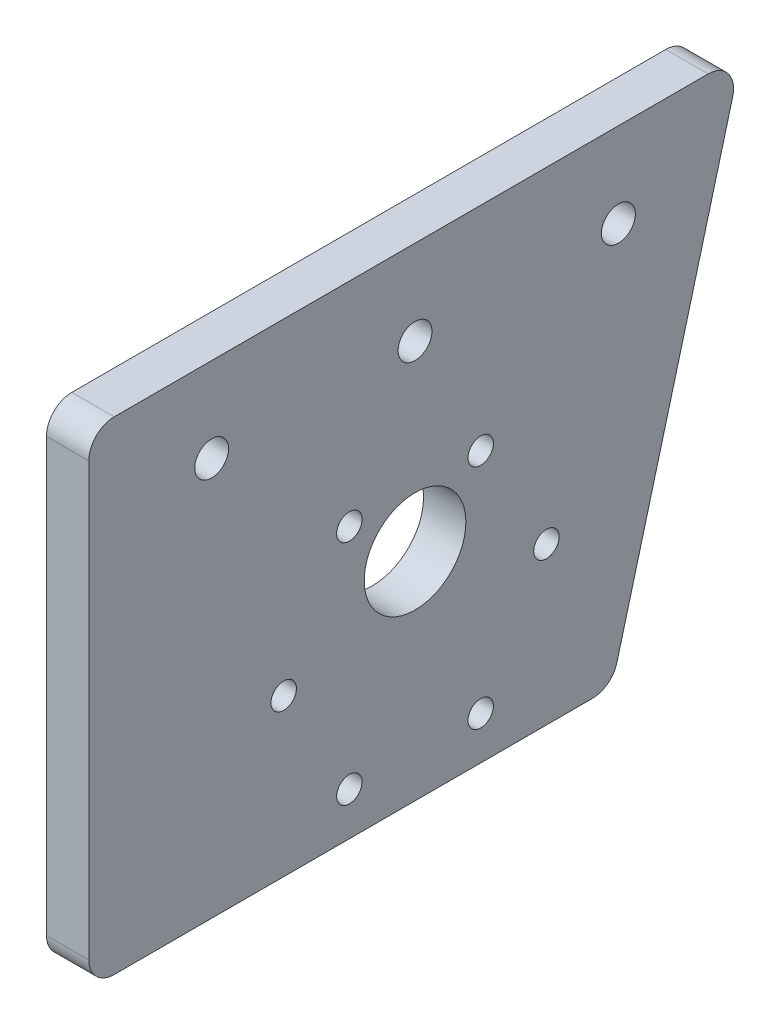
SolidWorks part; units mm, degrees
ref_plane "Front Plane" through (0, 0, 0) normal (0, 0, 1) x (1, 0, 0)
ref_plane "Top Plane" through (0, 0, 0) normal (0, 1, 0) x (1, 0, 0)
ref_plane "Right Plane" through (0, 0, 0) normal (1, 0, 0) x (0, 0, -1)
sketch "Sketch1" plane through (0, 0, 0) normal (1, 0, 0) x (0, 0, -1)
  line L0 (0, 0) -> (77, 0)
  line L1 (77, 0) -> (61.7269, -57)
  line L2 (61.7269, -57) -> (0, -57)
  line L3 (0, -57) -> (0, 0)
  line L4 (20, 0) -> (20, -57) construction
  line L5 (57, 0) -> (57, -57) construction
  line L6 (0, -20) -> (71.641, -20) construction
  line L7 (20, -20) -> (57, -57) construction
  line L8 (20, -57) -> (57, -20) construction
  line L9 (38.5, -38.5) -> (38.5, -31.5) construction
  line L10 (0, -10) -> (74.3205, -10) construction
  line L11 (38.5, -31.5) -> (38.5, -10) construction
  line L12 (38.5, -38.5) -> (23, -38.5) construction
  circle A0 centre (38.5, -38.5) radius 18.5 construction
  circle A1 centre (38.5, -31.5) radius 6
  circle A2 centre (38.5, -10) radius 2
  circle A3 centre (62.5, -10) radius 2
  circle A4 centre (14.5, -10) radius 2
  circle A5 centre (23, -38.5) radius 1.5
  circle A6 centre (30.75, -25.0766) radius 1.5
  circle A7 centre (46.25, -25.0766) radius 1.5
  circle A8 centre (54, -38.5) radius 1.5
  circle A9 centre (46.25, -51.9234) radius 1.5
  circle A10 centre (30.75, -51.9234) radius 1.5
  dimension "D8" = 12
  dimension "D10" = 24
  dimension "D11" = 24
  dimension "D13" = 3
  dimension "D15" = 4
  dimension "D1" = 57
  dimension "D2" = 77
  dimension "D3" = 75
  dimension "D4" = 20
  dimension "D5" = 20
  dimension "D6" = 20
  dimension "D7" = 7
  dimension "D9" = 10
  dimension "D12" = 15.5
  dimension "D14" = 6
extrude "Boss-Extrude1" add sketch "Sketch1" along normal blind 5
fillet "Fillet1" radius 3 4 edges at (2.5, 0, 0) (2.5, -57, 0) (2.5, -57, -61.7269) (2.5, 0, -77)
